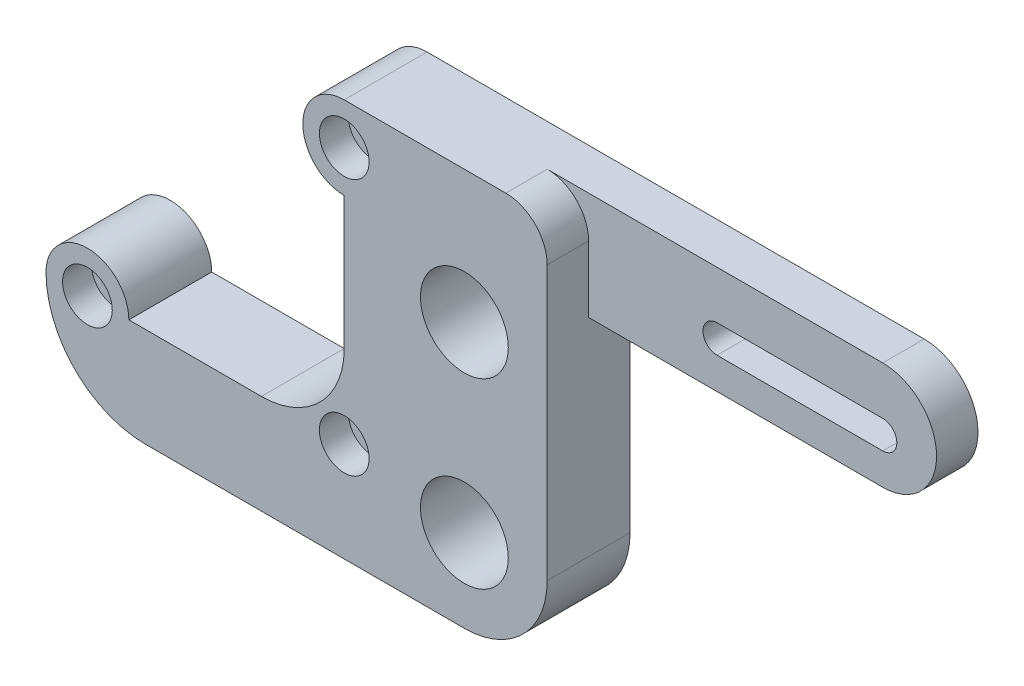
SolidWorks part; units mm, degrees
ref_plane "Front Plane" through (0, 0, 0) normal (0, 0, 1) x (1, 0, 0)
ref_plane "Top Plane" through (0, 0, 0) normal (0, 1, 0) x (1, 0, 0)
ref_plane "Right Plane" through (0, 0, 0) normal (1, 0, 0) x (0, 0, -1)
sketch "Sketch1" plane through (0, 0, 0) normal (0, 0, 1) x (1, 0, 0)
  line L0 (0, -5) -> (0, 5) construction
  line L1 (0, 5) -> (60, 5)
  line L2 (60, 5) -> (60, -8) construction
  line L3 (60, -2.5) -> (40, -2.5) construction
  line L4 (60, -8) -> (24.5, -8)
  line L5 (60, -4.2) -> (40, -4.2)
  line L6 (60, -0.8) -> (40, -0.8)
  line L7 (24.5, -8) -> (24.5, -33)
  line L8 (9.2, -33) -> (19.8, -33) construction
  line L9 (14.5, -11) -> (14.5, -33) construction
  line L10 (0, -5) -> (0, -21)
  line L11 (-10, -31) -> (0, -31) construction
  line L12 (-31, -31) -> (-26, -31) construction
  line L13 (14.5, -43) -> (-24, -43)
  line L14 (-10, -31) -> (-26, -31)
  line L15 (0, -31) -> (0, -21) construction
  line L16 (14.5, -33) -> (14.5, -43) construction
  line L17 (-31, -31) -> (-36, -31) construction
  arc A0 (0, 5) -> (0, -5) centre (0, 0) ccw
  circle A1 centre (0, 0) radius 1.8
  arc A2 (60, -8) -> (60, 5) centre (60, -1.5) ccw
  arc A3 (60, -4.2) -> (60, -0.8) centre (60, -2.5) ccw
  arc A4 (40, -0.8) -> (40, -4.2) centre (40, -2.5) ccw
  circle A5 centre (14.5, -33) radius 5.3
  circle A6 centre (14.5, -11) radius 5.3
  circle A7 centre (0, -31) radius 1.8
  arc A8 (-26, -31) -> (-36, -31) centre (-31, -31) ccw
  circle A9 centre (-31, -31) radius 1.8
  arc A10 (14.5, -43) -> (24.5, -33) centre (14.5, -33) ccw
  arc A11 (-10, -31) -> (0, -21) centre (-10, -21) ccw
  arc A12 (-36, -31) -> (-24, -43) centre (-24, -31) ccw
  point P14 (50, -2.5)
  point P28 (-35.9194, -30.1059)
  point P36 (0, 0)
  dimension "D1" = 10
  dimension "D2" = 3.6
  dimension "D4" = 20
  dimension "D8" = 10.6
  dimension "D9" = 22
  dimension "D10" = 31
  dimension "D12" = 20
  dimension "D13" = 1
  dimension "D7" = 2
  dimension "D11" = 42
  dimension "D5" = 1.7
  dimension "D3" = 60
  dimension "D6" = 25
extrude "Boss-Extrude1" add sketch "Sketch1" along normal blind 10
sketch "Sketch2" plane through (0, 0, 10) normal (0, 0, 1) x (1, 0, 0)
  circle A0 centre (-31, -31) radius 3
  circle A1 centre (0, -31) radius 3
  circle A2 centre (0, 0) radius 3
  dimension "D1" = 6
extrude "Cut-Extrude1" cut sketch "Sketch2" against normal blind 3.5
sketch "Sketch3" plane through (0, 0, 10) normal (0, 0, 1) x (1, 0, 0)
  line L0 (24.5, -8) -> (24.5, 0)
  line L1 (19.5, 5) -> (60, 5)
  line L2 (0, 5) -> (60, 5) construction
  line L3 (24.5, -8) -> (60, -8)
  arc A0 (60, 5) -> (60, -8) centre (60, -1.5) cw
  arc A1 (24.5, 0) -> (19.5, 5) centre (19.5, 0) ccw
  dimension "D1" = 5
extrude "Cut-Extrude2" cut sketch "Sketch3" against normal blind 5
